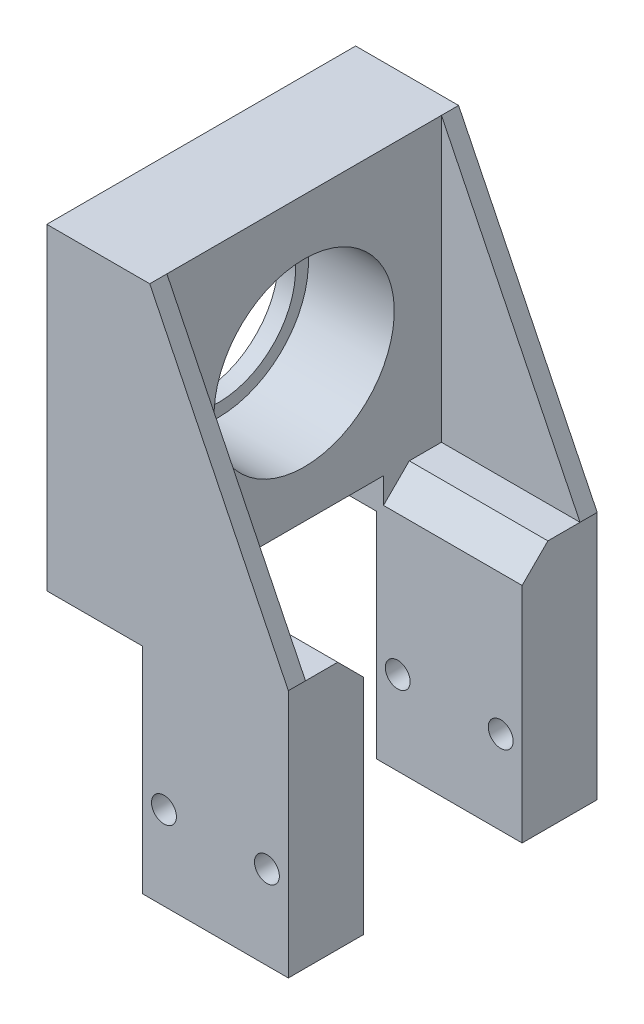
SolidWorks part; units mm, degrees
material "6061 Alloy"
ref_plane "Front Plane" through (0, 0, 0) normal (0, 0, 1) x (1, 0, 0)
ref_plane "Top Plane" through (0, 0, 0) normal (0, 1, 0) x (1, 0, 0)
ref_plane "Right Plane" through (0, 0, 0) normal (1, 0, 0) x (0, 0, -1)
sketch "Sketch1" plane through (0, 0, 0) normal (0, 0, 1) x (1, 0, 0)
  line L0 (0, 0) -> (17, 0)
  line L1 (17, 0) -> (17, 29)
  line L2 (17, 29) -> (0.8434, 29)
  line L3 (0.8434, 29) -> (0.8434, 62)
  line L4 (0.8434, 62) -> (-11.1566, 62)
  line L5 (-11.1566, 62) -> (-11.1566, 25)
  line L6 (-11.1566, 25) -> (0, 25)
  line L7 (0, 25) -> (0, 0)
  dimension "D1" = 17
  dimension "D2" = 62
  dimension "D3" = 25
  dimension "D4" = 12
  dimension "D5" = 4
extrude "Boss-Extrude1" add sketch "Sketch1" along normal blind 36
sketch "Sketch2" plane through (0.8434, 0, 0) normal (1, 0, 0) x (0, 0, -1)
  line L0 (-18, 62) -> (-18, 12.1467) construction
  line L1 (-36, 62) -> (0, 62) construction
  circle A0 centre (-18, 45) radius 10.5
  dimension "D1" = 21
  dimension "D2" = 17
extrude "Cut-Extrude1" cut sketch "Sketch2" against normal through all
sketch "Sketch3" plane through (17, 0, 0) normal (1, 0, 0) x (0, 0, -1)
  line L0 (-36, 0) -> (0, 0) construction
  line L1 (-27.25, 0) -> (-8.75, 0)
  line L2 (-27.25, 0) -> (-27.25, 29)
  line L3 (-27.25, 29) -> (-8.75, 29)
  line L4 (-8.75, 0) -> (-8.75, 29)
  line L5 (-36, 29) -> (0, 29) construction
  line L6 (-18, 0) -> (-18, 45) construction
  dimension "D1" = 18.5
extrude "Cut-Extrude2" cut sketch "Sketch3" against normal through all
sketch "Sketch4" plane through (0, 0, 36) normal (0, 0, 1) x (1, 0, 0)
  line L0 (0.8434, 62) -> (17, 29)
rib "Rib1" sketch "Sketch4" sketch "Sketch4" thickness 2 extrusion direction parallel to sketch draft on no parameters "D1"=2
sketch "Sketch5" plane through (0, 0, 0) normal (0, 0, -1) x (-1, 0, 0)
  line L0 (-0.8434, 62) -> (-17, 29)
rib "Rib2" sketch "Sketch5" sketch "Sketch5" thickness 2 extrusion direction parallel to sketch draft on no parameters "D1"=2
chamfer "Chamfer1" distance 3 angle 45 2 edges at (8.9217, 29, 27.25) (8.9217, 29, 8.75)
sketch "Sketch6" plane through (-11.1566, 0, 0) normal (-1, 0, 0) x (0, 0, 1)
  circle A0 centre (18, 45) radius 10.5 construction
  circle A1 centre (18, 45) radius 10.5
  circle A2 centre (18, 45) radius 9
  dimension "D1" = 1.5
extrude "Boss-Extrude2" add sketch "Sketch6" against normal blind 2
sketch "Sketch9" plane through (0, 0, 36) normal (0, 0, 1) x (1, 0, 0)
  line L0 (2.5, 9.75) -> (14.5, 9.75) construction
  line L2 (0, 0) -> (17, 0) construction
  line L3 (8.5, 0) -> (8.5, 9.75) construction
  line L4 (-11.1566, 25) -> (0, 25) construction
  point P0 (2.5, 9.75)
  point P2 (14.5, 9.75)
  dimension "D1" = 12
  dimension "D2" = 15.25
hole_wizard "M2.5 Clearance Hole1" positions "Sketch9" profile "Sketch8" hole size "M2.5" standard "DIN" end condition through all
sketch "Sketch8" plane through (2.5, 9.75, 36) normal (1, 0, 0) x (0, -1, 0)
  line L0 (0, 0) -> (0, 36)
  line L1 (0, 36) -> (1.45, 36)
  line L2 (1.45, 36) -> (1.45, 0)
  line L5 (1.45, 0) -> (0, 0)
  line L11 (0, -6.35) -> (0, 107.95) construction
  dimension "Thru Hole Dia." = 2.9
  dimension "Thru Hole Depth" = 36
sketch "Sketch10" plane through (-11.1566, 0, 0) normal (-1, 0, 0) x (0, 0, 1)
  circle A0 centre (18, 45) radius 11
  circle A1 centre (18, 45) radius 15
  dimension "D1" = 22
  dimension "D2" = 30
extrude "Cut-Extrude4" cut sketch "Sketch10" against normal blind 0.6
